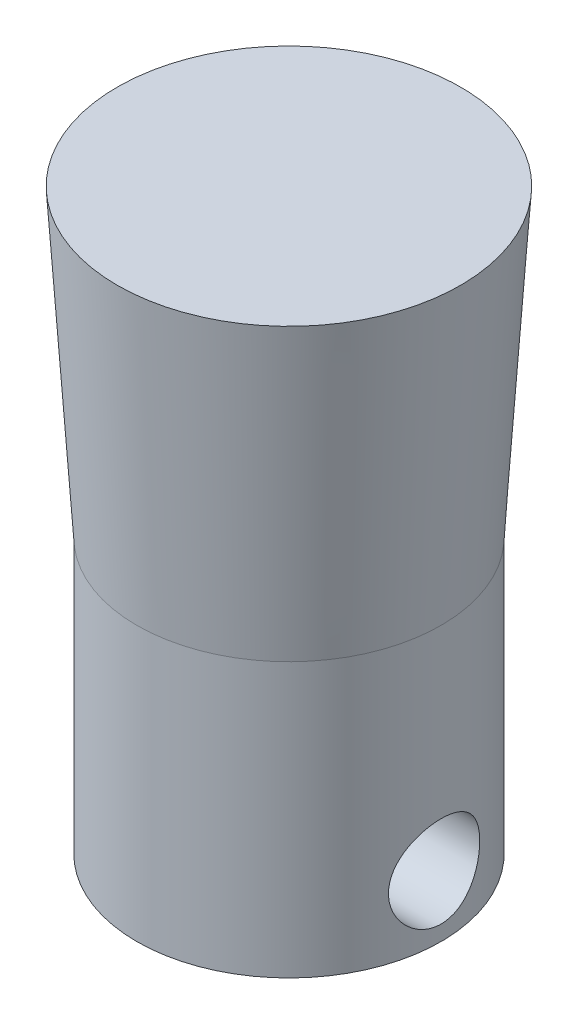
SolidWorks part; units mm, degrees
ref_plane "Front Plane" through (0, 0, 0) normal (0, 0, 1) x (1, 0, 0)
ref_plane "Top Plane" through (0, 0, 0) normal (0, 1, 0) x (1, 0, 0)
ref_plane "Right Plane" through (0, 0, 0) normal (1, 0, 0) x (0, 0, -1)
sketch "Sketch1" plane through (0, 0, 0) normal (0, 1, 0) x (1, 0, 0)
  circle A0 centre (0, 0) radius 5
  dimension "D1" = 10
extrude "body" add sketch "Sketch1" along normal blind 9
sketch "Sketch2" plane through (0, 0, 0) normal (1, 0, 0) x (0, 0, -1)
  circle A0 centre (0, 2) radius 1.5
  dimension "D1" = 2
  dimension "D2" = 3
extrude "pin insert" cut sketch "Sketch2" against normal through all and the other way through all
ref_plane "contact plane" through (0, 19, 0) normal (0, 1, 0) x (1, 0, 0)
sketch "head SA" plane through (0, 19, 0) normal (0, 1, 0) x (1, 0, 0)
  circle A0 centre (0, 0) radius 5.642
  dimension "D1" = 11.284
loft "cone" add profiles "head SA" section "head SA" section face at (0, 9, 5)
